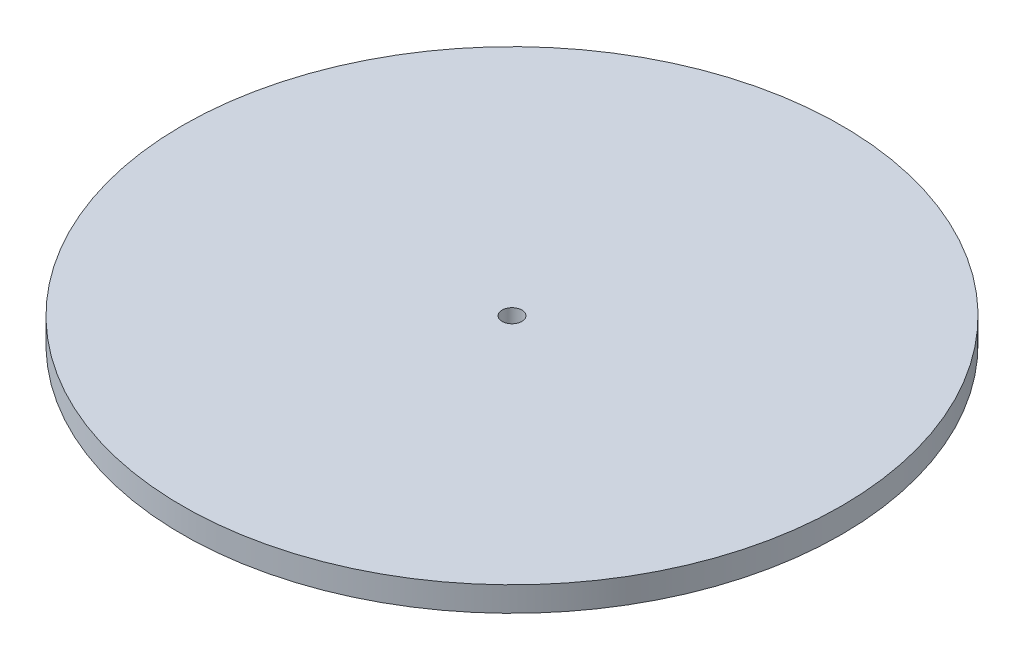
SolidWorks part; units mm, degrees
ref_plane "Front Plane" through (0, 0, 0) normal (0, 0, 1) x (1, 0, 0)
ref_plane "Top Plane" through (0, 0, 0) normal (0, 1, 0) x (1, 0, 0)
ref_plane "Right Plane" through (0, 0, 0) normal (1, 0, 0) x (0, 0, -1)
sketch "Sketch3" plane through (0, 0, 0) normal (0, 0, 1) x (1, 0, 0)
  line L0 (37, 8.4782) -> (37, 12.4782) construction
  line L1 (37, 12.4782) -> (0, 12.4782) construction
  line L2 (0, 12.4782) -> (0, 0) construction
  line L4 (1.2, 12.4782) -> (1.2, 7.4782)
  line L5 (1.2, 7.4782) -> (0, 7.4782)
  line L6 (0, 7.4782) -> (0, 0)
  line L7 (37, 8.4782) -> (40, 8.4782) construction
  line L8 (40, 8.4782) -> (40, 12.4782) construction
  line L9 (40, 12.4782) -> (1.2, 12.4782)
  line L10 (37, 8.4782) -> (37, 9.4782)
  line L11 (37, 9.4782) -> (40, 9.4782)
  line L12 (40, 9.4782) -> (40, 12.4782)
  spline S0 degree 8 poles (-3.7, 0.1581) (1.8454, -0.2895) (7.3908, -0.1563) (12.9361, 1.7257) (18.4815, 2.9916) (24.0269, 4.8086) (29.5723, 6.3353) (35.1177, 7.9713) (40.6631, 9.5067) knots 0 0 0 0 0 0 0 0 0 1 1 1 1 1 1 1 1 1 construction
  spline S1 degree 8 poles (0, 0) (4.625, 0.0011) (9.25, 0.6074) (13.875, 1.8873) (18.5, 3.1091) (23.125, 4.4906) (27.75, 5.8258) (32.375, 7.1664) (37, 8.4782) knots 0.083403 0.083403 0.083403 0.083403 0.083403 0.083403 0.083403 0.083403 0.083403 0.91743 0.91743 0.91743 0.91743 0.91743 0.91743 0.91743 0.91743 0.91743
  dimension "D1" = 3
  dimension "D2" = 1.2
  dimension "D3" = 5
  dimension "D4" = 3
  dimension "D5" = 40
  dimension "D6" = 8.4782
  dimension "D7" = 37
  dimension "D8" = 4
revolve "Revolve4" add sketch "Sketch3" angle 360 about L2
sketch "Sketch5" plane through (0, 12.4782, 0) normal (0, 1, 0) x (1, 0, 0)
  circle A0 centre (0, 0) radius 1.2
  circle A2 centre (0, 0) radius 1.2 construction
extrude "Cut-Extrude1" cut sketch "Sketch5" against normal through all
